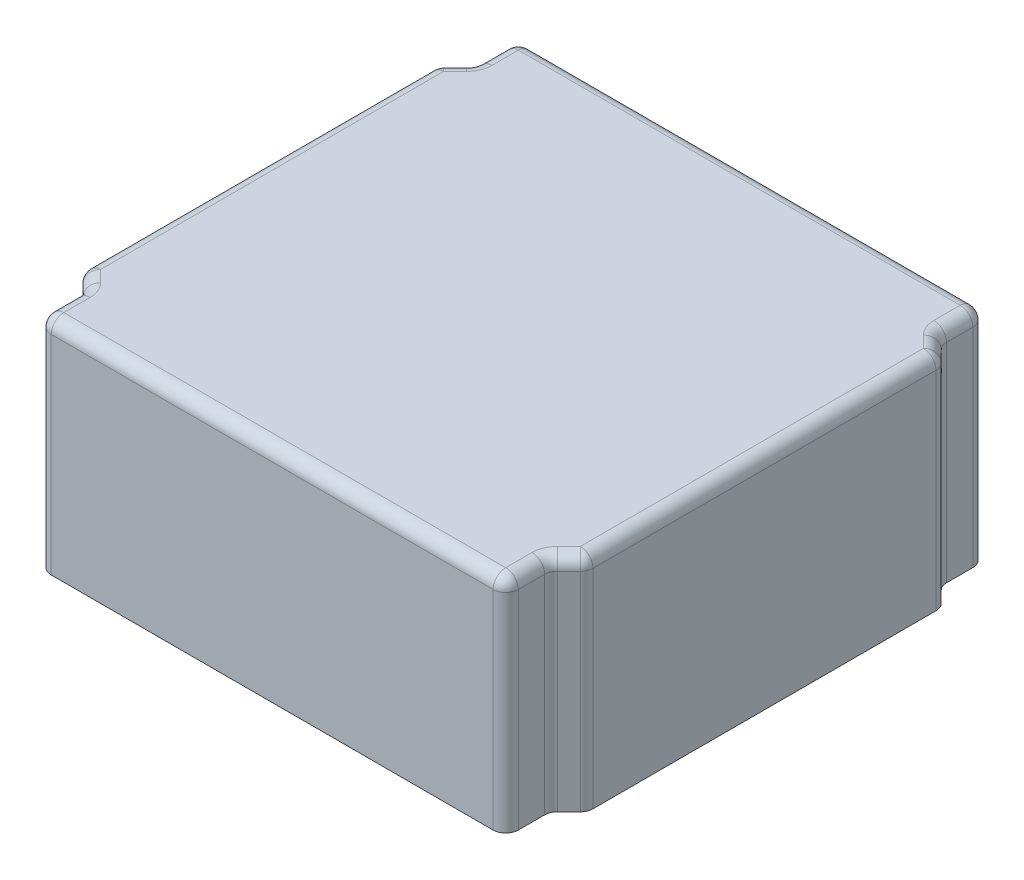
SolidWorks part; units mm, degrees
ref_plane "Спереди" through (0, 0, 0) normal (0, 0, 1) x (1, 0, 0)
ref_plane "Сверху" through (0, 0, 0) normal (0, 1, 0) x (1, 0, 0)
ref_plane "Справа" through (0, 0, 0) normal (1, 0, 0) x (0, 0, -1)
sketch "Эскиз1" plane through (0, 0, 0) normal (0, 1, 0) x (1, 0, 0)
  line L0 (-1.85, 1.9) -> (-1.85, 1.55)
  line L1 (2, -1.9) -> (-2, -1.9) construction
  line L2 (2, -1.9) -> (2, 1.9) construction
  line L3 (2, 1.9) -> (-2, 1.9) construction
  line L4 (-2, -1.9) -> (-2, 1.9) construction
  line L5 (2, -1.9) -> (-2, 1.9) construction
  line L6 (2, 1.9) -> (-2, -1.9) construction
  line L8 (-2, 1.4) -> (-2, -1.4)
  line L10 (-1.85, -1.55) -> (-1.85, -1.9)
  line L11 (1.85, -1.9) -> (1.85, -1.55)
  line L13 (2, -1.4) -> (2, 1.4)
  line L15 (1.85, 1.55) -> (1.85, 1.9)
  line L16 (-1.85, 1.9) -> (1.85, 1.9)
  line L17 (1.85, -1.9) -> (-1.85, -1.9)
  line L18 (2, 1.4) -> (1.85, 1.55)
  line L19 (2, -1.4) -> (1.85, -1.55)
  line L20 (-2, -1.4) -> (-1.85, -1.55)
  line L21 (-2, 1.4) -> (-1.85, 1.55)
  point P0 (0, 0)
  dimension "D1" = 3.8
  dimension "D2" = 4
extrude "Бобышка-Вытянуть2" add sketch "Эскиз1" along normal blind 1.75 contours L13 L18 L15 L16 L0 L21 L8 L20 L10 L17 L11 L19
fillet "Скругление1" radius 0.1 24 edges at (1.85, 1.75, 1.725) (0, 1.75, 1.9) (-1.85, 1.75, 1.725) (-2, 1.75, 0) (-1.85, 1.75, -1.725) (0, 1.75, -1.9) (1.85, 1.75, -1.725) (2, 1.75, 0) (1.85, 0.875, -1.9) (1.85, 0.875, 1.9) (-1.85, 0.875, 1.9) (-1.85, 0.875, -1.9) (1.925, 1.75, 1.475) (2, 0.875, 1.4) (1.85, 0.875, -1.55) (2, 0.875, -1.4) (-2, 0.875, -1.4) (-1.85, 0.875, -1.55) (-1.85, 0.875, 1.55) (-2, 0.875, 1.4) (-1.925, 1.75, 1.475) (-1.925, 1.75, -1.475) (1.925, 1.75, -1.475) (1.85, 0.875, 1.55)
